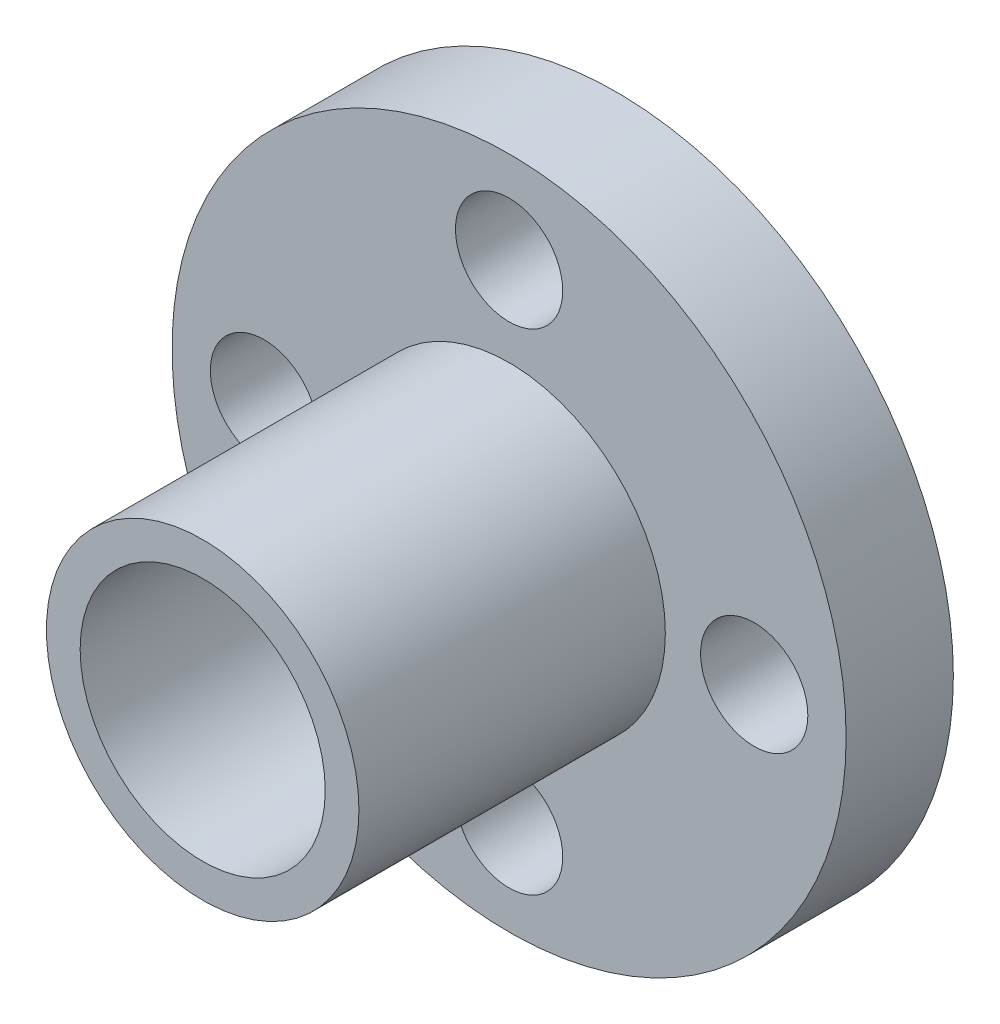
SolidWorks part; units mm, degrees
ref_plane "前视基准面" through (0, 0, 0) normal (0, 0, 1) x (1, 0, 0)
ref_plane "上视基准面" through (0, 0, 0) normal (0, 1, 0) x (1, 0, 0)
ref_plane "右视基准面" through (0, 0, 0) normal (1, 0, 0) x (0, 0, -1)
sketch "草图1" plane through (0, 0, 0) normal (0, 0, 1) x (1, 0, 0)
  circle A0 centre (0, 0) radius 11
  dimension "D1" = 22
extrude "凸台-拉伸1" add sketch "草图1" along normal blind 3.5
sketch "草图2" plane through (0, 0, 3.5) normal (0, 0, 1) x (1, 0, 0)
  circle A0 centre (0, 0) radius 5.1
  dimension "D1" = 10.2
extrude "凸台-拉伸2" add sketch "草图2" along normal blind 10
sketch "草图3" plane through (0, 0, 0) normal (0, 0, -1) x (-1, 0, 0)
  circle A0 centre (0, 0) radius 5.1
  dimension "D1" = 10.2
extrude "凸台-拉伸3" add sketch "草图3" along normal blind 1.5
sketch "草图4" plane through (0, 0, 0) normal (0, 0, -1) x (-1, 0, 0)
  circle A0 centre (0, 0) radius 8 construction
  circle A1 centre (0, 8) radius 1.75
  circle A2 centre (8, 0) radius 1.75
  circle A3 centre (0, -8) radius 1.75
  circle A4 centre (-8, 0) radius 1.75
  point P14 (0, 0)
  dimension "D1" = 16
  dimension "D2" = 1.75
  dimension "D3" = 4
extrude "切除-拉伸1" cut sketch "草图4" against normal through all both and the other way through all
sketch "草图5" plane through (0, 0, -1.5) normal (0, 0, -1) x (-1, 0, 0)
  circle A0 centre (0, 0) radius 4
  dimension "D1" = 8
extrude "切除-拉伸2" cut sketch "草图5" against normal through all both and the other way through all
